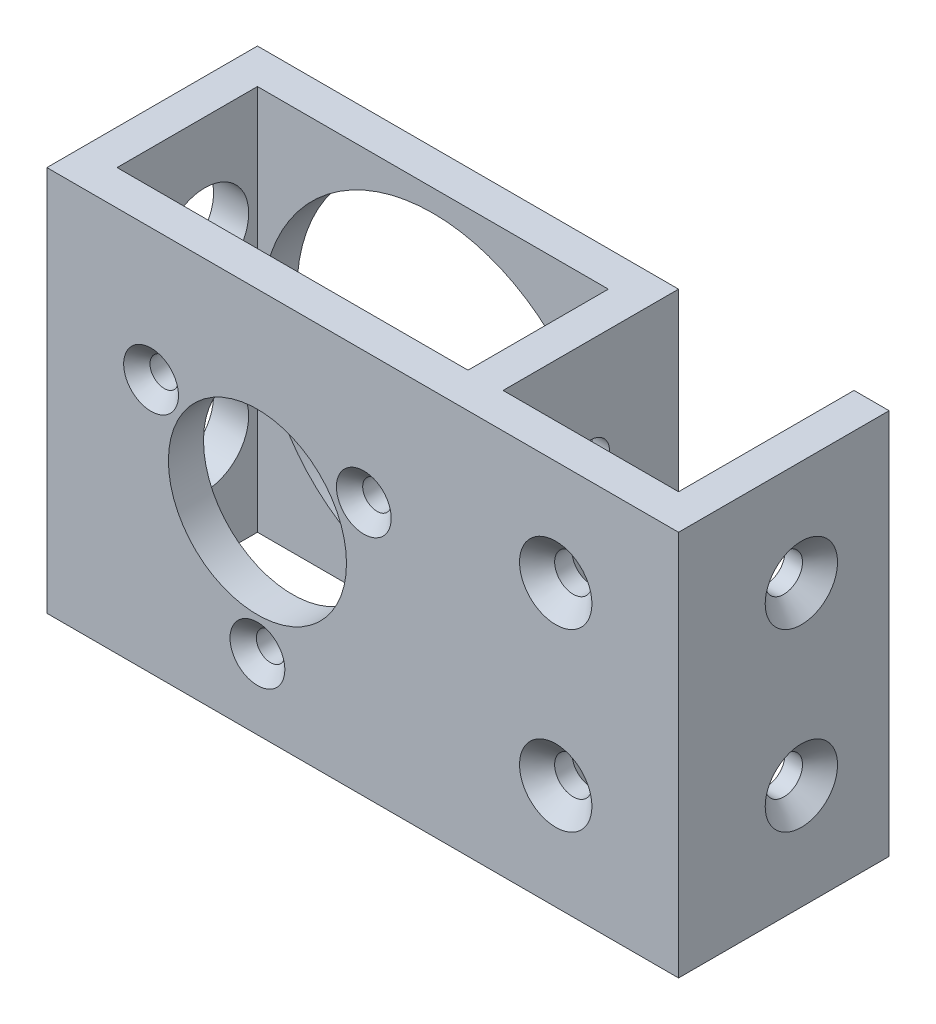
SolidWorks part; units mm, degrees
ref_plane "Front Plane" through (0, 0, 0) normal (0, 0, 1) x (1, 0, 0)
ref_plane "Top Plane" through (0, 0, 0) normal (0, 1, 0) x (1, 0, 0)
ref_plane "Right Plane" through (0, 0, 0) normal (1, 0, 0) x (0, 0, -1)
sketch "Sketch1" plane through (0, 0, 0) normal (0, 1, 0) x (1, 0, 0)
  line L0 (0, 0) -> (0, 20)
  line L1 (0, 0) -> (-20, 0)
  line L2 (-20, 0) -> (-20, 20)
  line L3 (0, 20) -> (4, 20)
  line L4 (4, 20) -> (4, -4)
  line L5 (4, -4) -> (-24, -4)
  line L6 (-24, 0) -> (-24, 16)
  line L7 (-24, 20) -> (-20, 20)
  line L8 (-24, -4) -> (-68, -4)
  line L9 (-68, -4) -> (-68, 0)
  line L10 (-64, 0) -> (-24, 0)
  line L11 (-24, 20) -> (-68, 20)
  line L12 (-68, 20) -> (-68, 16)
  line L13 (-64, 16) -> (-24, 16)
  line L14 (-68, 16) -> (-68, 0)
  line L15 (-64, 0) -> (-64, 16)
  dimension "D1" = 20
  dimension "D2" = 20
  dimension "D3" = 20
  dimension "D4" = 4
  dimension "D5" = 4
  dimension "D6" = 4
  dimension "D7" = 44
  dimension "D8" = 4
  dimension "D9" = 44
  dimension "D10" = 4
extrude "Boss-Extrude1" add sketch "Sketch1" along normal blind 44
sketch "Sketch3" plane through (0, 0, -20) normal (0, 0, -1) x (-1, 0, 0)
  line L0 (20, 0) -> (68, 0) construction
  line L1 (20, 44) -> (20, 0) construction
  circle A0 centre (44, 22) radius 19.5
  dimension "D1" = 39
  dimension "D2" = 22
  dimension "D3" = 24
extrude "Cut-Extrude1" cut sketch "Sketch3" against normal up to next
sketch "Sketch4" plane through (0, 0, 4) normal (0, 0, 1) x (1, 0, 0)
  line L0 (-68, 44) -> (4, 44) construction
  line L1 (-68, 44) -> (-68, 0) construction
  line L2 (-44, 22) -> (-56.1244, 29) construction
  line L3 (-44, 8) -> (-44, 22) construction
  line L4 (-44, 22) -> (-31.8756, 29) construction
  line L5 (-68, 0) -> (4, 0) construction
  circle A0 centre (-44, 22) radius 10.15
  circle A1 centre (-56.1244, 29) radius 1.625
  circle A2 centre (-31.8756, 29) radius 1.625
  circle A3 centre (-44, 8) radius 1.625
  dimension "D1" = 20.3
  dimension "D4" = 3.25
  dimension "D5" = 3.25
  dimension "D6" = 3.25
  dimension "D2" = 22
  dimension "D3" = 24
  dimension "D7" = 14
  dimension "D8" = 14
  dimension "D9" = 14
  dimension "D10" = 30
  dimension "D11" = 30
extrude "Cut-Extrude2" cut sketch "Sketch4" against normal up to next
sketch "Sketch5" plane through (4, 0, 0) normal (1, 0, 0) x (0, 0, -1)
  line L0 (-4, 44) -> (20, 44) construction
  line L1 (-4, 0) -> (20, 0) construction
  line L2 (20, 44) -> (20, 0) construction
  circle A0 centre (10, 32) radius 2.125
  circle A1 centre (10, 12) radius 2.125
  dimension "D1" = 4.25
  dimension "D2" = 4.25
  dimension "D3" = 12
  dimension "D4" = 12
  dimension "D5" = 10
  dimension "D6" = 10
extrude "Cut-Extrude3" cut sketch "Sketch5" against normal through all
sketch "Sketch6" plane through (0, 0, 4) normal (0, 0, 1) x (1, 0, 0)
  line L0 (4, 44) -> (4, 0) construction
  line L1 (-68, 44) -> (4, 44) construction
  line L2 (-68, 0) -> (4, 0) construction
  circle A0 centre (-10, 32) radius 2.125
  circle A1 centre (-10, 12) radius 2.125
  dimension "D1" = 4.25
  dimension "D2" = 4.25
  dimension "D3" = 14
  dimension "D4" = 14
  dimension "D5" = 12
  dimension "D6" = 12
extrude "Cut-Extrude4" cut sketch "Sketch6" against normal up to next
chamfer "Chamfer1" distance 2 6 edges at (4, 12, -12.125) (4, 32, -12.125) (-7.875, 12, 4) (-24, 32, -7.875) (-24, 12, -7.875) (-7.875, 32, 4)
chamfer "Chamfer2" distance 1.5 angle 45 3 edges at (-42.375, 8, 4) (-30.2506, 29, 4) (-54.4994, 29, 4)
sketch "Sketch7" plane through (-68, 0, 0) normal (-1, 0, 0) x (0, 0, 1)
  circle A0 centre (-10, 32) radius 5
  circle A1 centre (-10, 12) radius 5
  dimension "D1" = 10
  dimension "D2" = 10
extrude "Cut-Extrude5" cut sketch "Sketch7" against normal up to next
